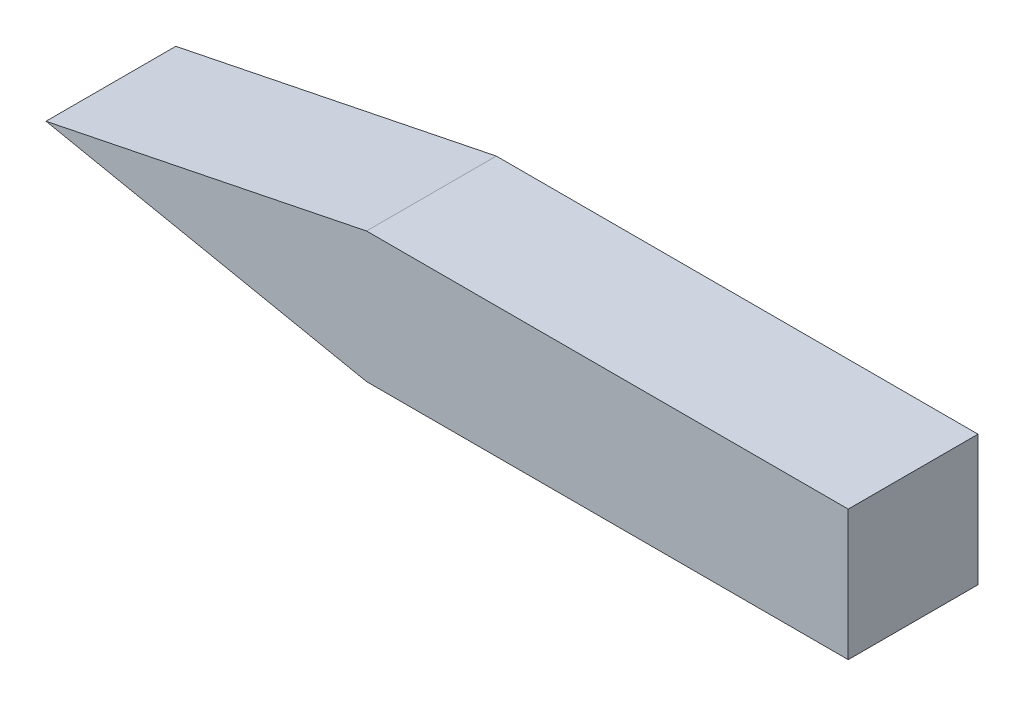
SolidWorks part; units mm, degrees
ref_plane "前基準面" through (0, 0, 0) normal (0, 0, 1) x (1, 0, 0)
ref_plane "上基準面" through (0, 0, 0) normal (0, 1, 0) x (1, 0, 0)
ref_plane "右基準面" through (0, 0, 0) normal (1, 0, 0) x (0, 0, -1)
sketch "草圖1" plane through (0, 0, 0) normal (0, 0, 1) x (1, 0, 0)
  line L0 (0, 0) -> (37.09, 0) construction
  line L1 (14.82, 0) -> (14.82, 3.0152)
  line L2 (0, 0) -> (14.82, 3.0152)
  line L3 (14.82, 3.0152) -> (37.09, 3.0152)
  line L4 (37.09, 3.0152) -> (37.09, -3.0152)
  line L5 (0, 0) -> (14.82, -3.0152)
  line L6 (14.82, -3.0152) -> (37.09, -3.0152)
  point P3 (14.82, 0)
  dimension "D1" = 37.09
  dimension "D2" = 14.82
  dimension "D3" = 11.5
extrude "填料-伸長1" add sketch "草圖1" along normal blind 6 contours L1 L0 L4 L3 | L0 L5 L6 L4
